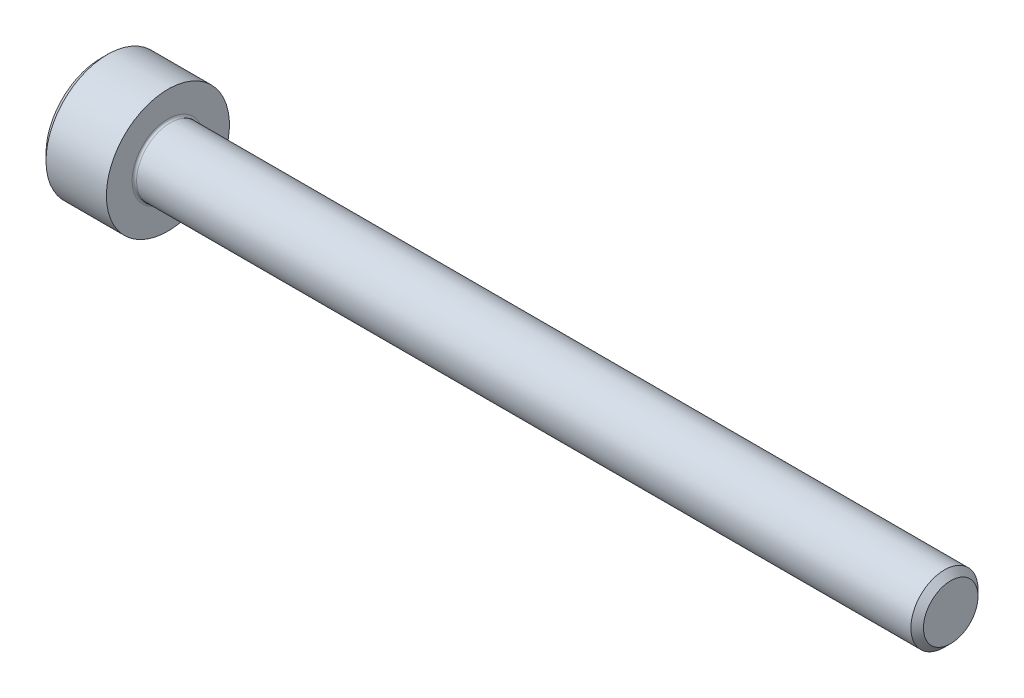
SolidWorks part; units mm, degrees
ref_plane "Front Plane" through (0, 0, 0) normal (0, 0, 1) x (1, 0, 0)
ref_plane "Top Plane" through (0, 0, 0) normal (0, 1, 0) x (1, 0, 0)
ref_plane "Right Plane" through (0, 0, 0) normal (1, 0, 0) x (0, 0, -1)
ref_plane "Plane1" through (3, 0, 0) normal (1, 0, 0) x (0, 0, -1)
sketch "Sketch1" plane through (3, 0, 0) normal (1, 0, 0) x (0, 0, -1)
  circle A0 centre (0, 0) radius 2.75
extrude "Boss-Extrude1" add sketch "Sketch1" against normal blind 3
sketch "Sketch2" plane through (3, 0, 0) normal (1, 0, 0) x (0, 0, -1)
  circle A0 centre (0, 0) radius 1.5
extrude "Boss-Extrude2" add sketch "Sketch2" along normal blind 35
sketch "Sketch3" plane through (0, 0, 0) normal (-1, 0, 0) x (0, 0, 1)
  line L0 (-1.28, 0.739) -> (-1.28, -0.739)
  line L1 (-1.28, -0.739) -> (0, -1.478)
  line L2 (0, -1.478) -> (1.28, -0.739)
  line L3 (1.28, -0.739) -> (1.28, 0.739)
  line L4 (1.28, 0.739) -> (0, 1.478)
  line L5 (0, 1.478) -> (-1.28, 0.739)
extrude "Cut-Extrude1" cut sketch "Sketch3" against normal blind 1.3
sketch "Sketch4" plane through (0, 0, 0) normal (0, 0, 1) x (1, 0, 0)
  line L0 (1.3, 1.28) -> (1.3, 0)
  line L1 (1.3, 0) -> (2.039, 0)
  line L2 (2.039, 0) -> (1.3, 1.28)
  line L3 (1.3, 0) -> (2.039, 0) construction
revolve "Cut-Revolve1" cut sketch "Sketch4" angle 360 about L3
fillet "Fillet1" radius 0.1 1 edges at (3, 0, -1.5)
chamfer "Chamfer1" distance 0.3 angle 45 1 edges at (0, 0, 2.75)
chamfer "Chamfer2" distance 0.2805 angle 45 1 edges at (38, 0, -1.5)
